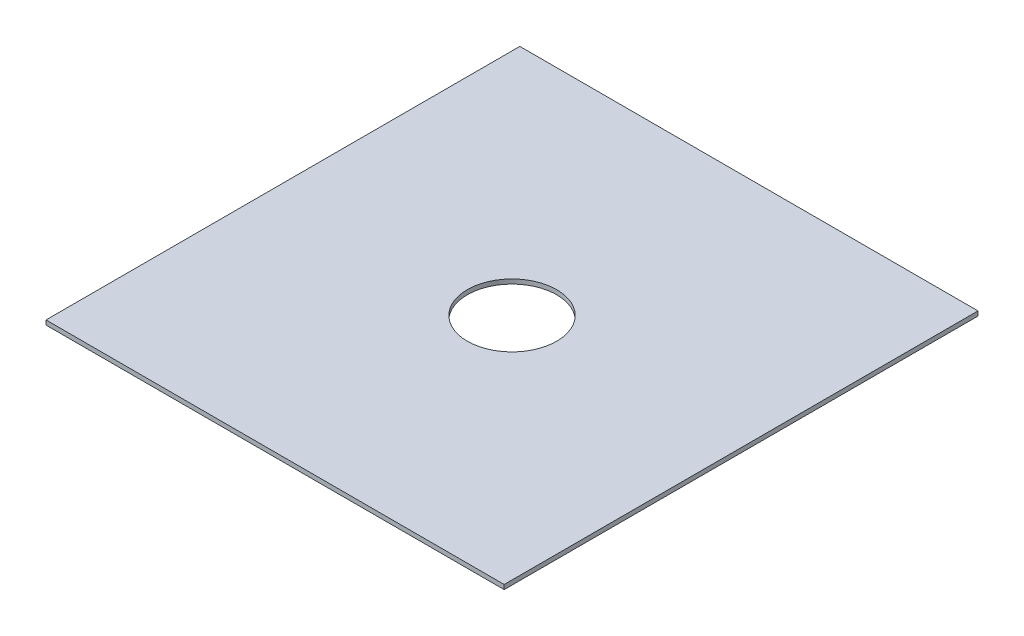
SolidWorks part; units mm, degrees
ref_plane "Front Plane" through (0, 0, 0) normal (0, 0, 1) x (1, 0, 0)
ref_plane "Top Plane" through (0, 0, 0) normal (0, 1, 0) x (1, 0, 0)
ref_plane "Right Plane" through (0, 0, 0) normal (1, 0, 0) x (0, 0, -1)
sketch "Sketch1" plane through (0, 0, 0) normal (0, 1, 0) x (1, 0, 0)
  line L1 (-162.7188, 168.275) -> (162.7187, 168.275)
  line L2 (-162.7188, 168.275) -> (-162.7187, -168.275)
  line L3 (-162.7187, -168.275) -> (162.7188, -168.275)
  line L4 (162.7187, 168.275) -> (162.7188, -168.275)
  line L5 (-162.7188, 168.275) -> (162.7188, -168.275) construction
  line L6 (-162.7187, -168.275) -> (162.7187, 168.275) construction
  point P0 (0, 0)
  dimension "D1" = 325.4375
  dimension "D2" = 336.55
extrude "Boss-Extrude1" add sketch "Sketch1" along normal blind 3.175
sketch "Sketch2" plane through (0, 3.175, 0) normal (0, 1, 0) x (1, 0, 0)
  circle A0 centre (0, 0) radius 31.75
  dimension "D1" = 63.5
extrude "Cut-Extrude1" cut sketch "Sketch2" against normal through all
